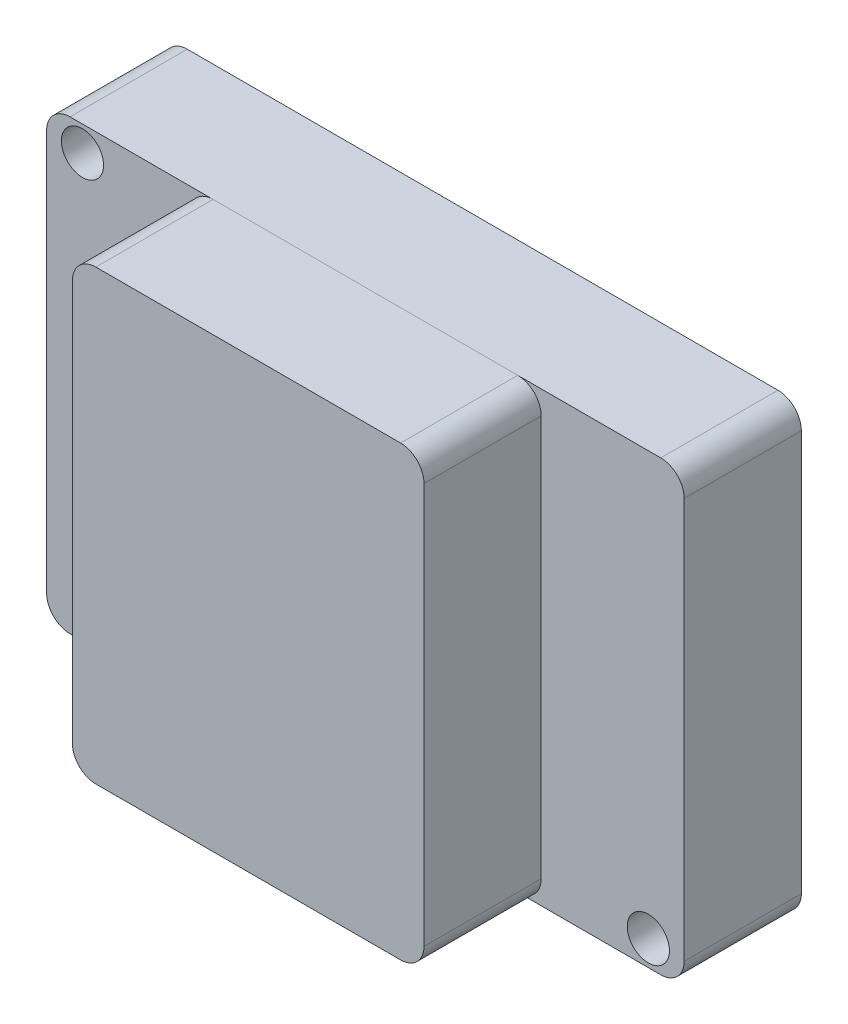
SolidWorks part; units mm, degrees
ref_plane "Front Plane" through (0, 0, 0) normal (0, 0, 1) x (1, 0, 0)
ref_plane "Top Plane" through (0, 0, 0) normal (0, 1, 0) x (1, 0, 0)
ref_plane "Right Plane" through (0, 0, 0) normal (1, 0, 0) x (0, 0, -1)
sketch "Sketch1" plane through (0, 0, 0) normal (0, 0, 1) x (1, 0, 0)
  line L0 (-30.6607, 21.5301) -> (-34.544, 24.257) construction
  line L1 (-34.544, -24.257) -> (34.544, -24.257)
  line L2 (-34.544, -24.257) -> (-34.544, 24.257)
  line L3 (-34.544, 24.257) -> (34.544, 24.257)
  line L4 (34.544, -24.257) -> (34.544, 24.257)
  line L5 (-34.544, -24.257) -> (34.544, 24.257) construction
  line L6 (-34.544, 24.257) -> (34.544, -24.257) construction
  line L7 (30.6607, -21.5301) -> (34.544, -24.257) construction
  line L8 (-28.7899, 20.2164) -> (28.7899, -20.2164) construction
  circle A0 centre (-30.6607, 21.5301) radius 2.286
  circle A1 centre (30.6607, -21.5301) radius 2.286
  point P0 (0, 0)
  dimension "D4" = 4.572
  dimension "D5" = 4.572
  dimension "D1" = 69.088
  dimension "D2" = 48.514
  dimension "D3" = 74.93
extrude "Boss-Extrude1" add sketch "Sketch1" along normal blind 12.7
sketch "Sketch2" plane through (0, 0, 12.7) normal (0, 0, 1) x (1, 0, 0)
  line L0 (34.544, 24.257) -> (-34.544, 24.257) construction
  line L1 (-19.05, -24.257) -> (19.05, -24.257)
  line L2 (-19.05, -24.257) -> (-19.05, 24.257)
  line L3 (-19.05, 24.257) -> (19.05, 24.257)
  line L4 (19.05, -24.257) -> (19.05, 24.257)
  line L5 (-19.05, -24.257) -> (19.05, 24.257) construction
  line L6 (-19.05, 24.257) -> (19.05, -24.257) construction
  point P0 (0, 0)
  dimension "D1" = 38.1
extrude "Boss-Extrude2" add sketch "Sketch2" along normal blind 12.7 separate body
fillet "Fillet1" radius 2.54 4 edges at (-34.544, 24.257, 6.35) (34.544, 24.257, 6.35) (34.544, -24.257, 6.35) (-34.544, -24.257, 6.35)
fillet "Fillet2" radius 2.54 4 edges at (-19.05, -24.257, 19.05) (-19.05, 24.257, 19.05) (19.05, 24.257, 19.05) (19.05, -24.257, 19.05)
